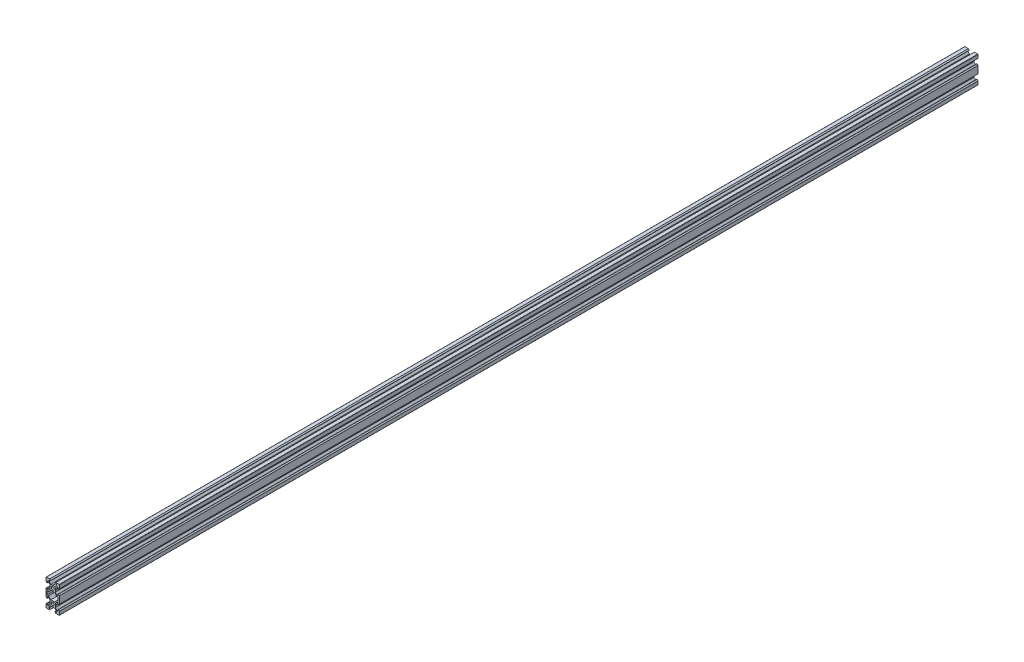
SolidWorks part; units mm, degrees
material "6061-T6 (SS)"
ref_plane "Front Plane" through (0, 0, 0) normal (0, 0, 1) x (1, 0, 0)
ref_plane "Top Plane" through (0, 0, 0) normal (0, 1, 0) x (1, 0, 0)
ref_plane "Right Plane" through (0, 0, 0) normal (1, 0, 0) x (0, 0, -1)
sketch "Sketch1" plane through (0, 0, 0) normal (0, 0, 1) x (1, 0, 0)
  line L0 (0, 0) -> (10, 0) construction
  line L1 (9.5, -20) -> (-9.5, -20)
  line L2 (10, -19.5) -> (10, 19.5)
  line L3 (9.5, 20) -> (-9.5, 20)
  line L4 (-10, -19.5) -> (-10, 19.5)
  line L5 (10, -20) -> (-10, 20) construction
  line L6 (10, 20) -> (-10, -20) construction
  circle A0 centre (0, 10) radius 2.1
  circle A1 centre (0, -10) radius 2.1
  arc A2 (-9.5, -20) -> (-10, -19.5) centre (-9.5, -19.5) cw
  arc A3 (9.5, -20) -> (10, -19.5) centre (9.5, -19.5) ccw
  arc A4 (10, 19.5) -> (9.5, 20) centre (9.5, 19.5) ccw
  arc A5 (-9.5, 20) -> (-10, 19.5) centre (-9.5, 19.5) ccw
  point P0 (0, 0)
  line B0 (0, 10) -> (0, 20) construction
  line B1 (0, 13.69) -> (-0.21, 13.9)
  line B2 (-0.21, 13.9) -> (-2.8393, 13.9)
  line B3 (-2.8393, 13.9) -> (-5.5, 16.5607)
  line B4 (-5.5, 16.5607) -> (-5.5, 18.2)
  line B5 (-5.5, 18.2) -> (-3.125, 18.2)
  line B6 (-3.125, 18.2) -> (-3.125, 18.545)
  line B7 (-3.125, 18.545) -> (-4.58, 20)
  line B8 (-4.58, 20) -> (4.58, 20)
  line B9 (0, 10) -> (-5.9132, 15.9132) construction
  line B10 (3.125, 18.545) -> (4.58, 20)
  line B11 (3.125, 18.2) -> (3.125, 18.545)
  line B12 (5.5, 18.2) -> (3.125, 18.2)
  line B13 (5.5, 16.5607) -> (5.5, 18.2)
  line B14 (2.8393, 13.9) -> (5.5, 16.5607)
  line B15 (0.21, 13.9) -> (2.8393, 13.9)
  line B16 (0, 13.69) -> (0.21, 13.9)
  line B17 (0, 10) -> (-10, 10) construction
  line B18 (-3.69, 10) -> (-3.9, 9.79)
  line B19 (-3.9, 9.79) -> (-3.9, 7.1607)
  line B20 (-3.9, 7.1607) -> (-6.5607, 4.5)
  line B21 (-6.5607, 4.5) -> (-8.2, 4.5)
  line B22 (-8.2, 4.5) -> (-8.2, 6.875)
  line B23 (-8.2, 6.875) -> (-8.545, 6.875)
  line B24 (-8.545, 6.875) -> (-10, 5.42)
  line B25 (-10, 5.42) -> (-10, 14.58)
  line B26 (0, 10) -> (-5.9132, 4.0868) construction
  line B27 (-8.545, 13.125) -> (-10, 14.58)
  line B28 (-8.2, 13.125) -> (-8.545, 13.125)
  line B29 (-8.2, 15.5) -> (-8.2, 13.125)
  line B30 (-6.5607, 15.5) -> (-8.2, 15.5)
  line B31 (-3.9, 12.8393) -> (-6.5607, 15.5)
  line B32 (-3.9, 10.21) -> (-3.9, 12.8393)
  line B33 (-3.69, 10) -> (-3.9, 10.21)
  line B34 (0, -10) -> (-10, -10) construction
  line B35 (-3.69, -10) -> (-3.9, -10.21)
  line B36 (-3.9, -10.21) -> (-3.9, -12.8393)
  line B37 (-3.9, -12.8393) -> (-6.5607, -15.5)
  line B38 (-6.5607, -15.5) -> (-8.2, -15.5)
  line B39 (-8.2, -15.5) -> (-8.2, -13.125)
  line B40 (-8.2, -13.125) -> (-8.545, -13.125)
  line B41 (-8.545, -13.125) -> (-10, -14.58)
  line B42 (-10, -14.58) -> (-10, -5.42)
  line B43 (0, -10) -> (-5.9132, -15.9132) construction
  line B44 (-8.545, -6.875) -> (-10, -5.42)
  line B45 (-8.2, -6.875) -> (-8.545, -6.875)
  line B46 (-8.2, -4.5) -> (-8.2, -6.875)
  line B47 (-6.5607, -4.5) -> (-8.2, -4.5)
  line B48 (-3.9, -7.1607) -> (-6.5607, -4.5)
  line B49 (-3.9, -9.79) -> (-3.9, -7.1607)
  line B50 (-3.69, -10) -> (-3.9, -9.79)
  line B51 (0, -10) -> (0, -20) construction
  line B52 (0, -13.69) -> (0.21, -13.9)
  line B53 (0.21, -13.9) -> (2.8393, -13.9)
  line B54 (2.8393, -13.9) -> (5.5, -16.5607)
  line B55 (5.5, -16.5607) -> (5.5, -18.2)
  line B56 (5.5, -18.2) -> (3.125, -18.2)
  line B57 (3.125, -18.2) -> (3.125, -18.545)
  line B58 (3.125, -18.545) -> (4.58, -20)
  line B59 (4.58, -20) -> (-4.58, -20)
  line B60 (0, -10) -> (5.9132, -15.9132) construction
  line B61 (-3.125, -18.545) -> (-4.58, -20)
  line B62 (-3.125, -18.2) -> (-3.125, -18.545)
  line B63 (-5.5, -18.2) -> (-3.125, -18.2)
  line B64 (-5.5, -16.5607) -> (-5.5, -18.2)
  line B65 (-2.8393, -13.9) -> (-5.5, -16.5607)
  line B66 (-0.21, -13.9) -> (-2.8393, -13.9)
  line B67 (0, -13.69) -> (-0.21, -13.9)
  line B68 (0, -10) -> (10, -10) construction
  line B69 (3.69, -10) -> (3.9, -9.79)
  line B70 (3.9, -9.79) -> (3.9, -7.1607)
  line B71 (3.9, -7.1607) -> (6.5607, -4.5)
  line B72 (6.5607, -4.5) -> (8.2, -4.5)
  line B73 (8.2, -4.5) -> (8.2, -6.875)
  line B74 (8.2, -6.875) -> (8.545, -6.875)
  line B75 (8.545, -6.875) -> (10, -5.42)
  line B76 (10, -5.42) -> (10, -14.58)
  line B77 (0, -10) -> (5.9132, -4.0868) construction
  line B78 (8.545, -13.125) -> (10, -14.58)
  line B79 (8.2, -13.125) -> (8.545, -13.125)
  line B80 (8.2, -15.5) -> (8.2, -13.125)
  line B81 (6.5607, -15.5) -> (8.2, -15.5)
  line B82 (3.9, -12.8393) -> (6.5607, -15.5)
  line B83 (3.9, -10.21) -> (3.9, -12.8393)
  line B84 (3.69, -10) -> (3.9, -10.21)
  line B85 (0, 10) -> (10, 10) construction
  line B86 (3.69, 10) -> (3.9, 10.21)
  line B87 (3.9, 10.21) -> (3.9, 12.8393)
  line B88 (3.9, 12.8393) -> (6.5607, 15.5)
  line B89 (6.5607, 15.5) -> (8.2, 15.5)
  line B90 (8.2, 15.5) -> (8.2, 13.125)
  line B91 (8.2, 13.125) -> (8.545, 13.125)
  line B92 (8.545, 13.125) -> (10, 14.58)
  line B93 (10, 14.58) -> (10, 5.42)
  line B94 (0, 10) -> (5.9132, 15.9132) construction
  line B95 (8.545, 6.875) -> (10, 5.42)
  line B96 (8.2, 6.875) -> (8.545, 6.875)
  line B97 (8.2, 4.5) -> (8.2, 6.875)
  line B98 (6.5607, 4.5) -> (8.2, 4.5)
  line B99 (3.9, 7.1607) -> (6.5607, 4.5)
  line B100 (3.9, 9.79) -> (3.9, 7.1607)
  line B101 (3.69, 10) -> (3.9, 9.79)
  line B102 (-8.2, -2.7) -> (-8.2, 2.7)
  line B103 (-8.2, 2.7) -> (-6.2393, 2.7)
  line B104 (-6.2393, 2.7) -> (-2.8393, 6.1)
  line B105 (-2.8393, 6.1) -> (2.8393, 6.1)
  line B106 (0, 6.1) -> (0, 0) construction
  line B107 (0, 0) -> (-8.2, 0) construction
  line B108 (6.2393, 2.7) -> (2.8393, 6.1)
  line B109 (8.2, 2.7) -> (6.2393, 2.7)
  line B110 (8.2, -2.7) -> (8.2, 2.7)
  line B111 (8.2, -2.7) -> (6.2393, -2.7)
  line B112 (6.2393, -2.7) -> (2.8393, -6.1)
  line B113 (-2.8393, -6.1) -> (2.8393, -6.1)
  line B114 (-6.2393, -2.7) -> (-2.8393, -6.1)
  line B115 (-8.2, -2.7) -> (-6.2393, -2.7)
  line B116 (0, 6.1) -> (0, 10) construction
  line B117 (0, 10) -> (-5.0927, 4.9073) construction
  dimension "D4" = 4.2
  dimension "D5" = 0.5
  dimension "D1" = 20
  dimension "D2" = 40
  dimension "D3" = 20
sketch_block_instance "V Slot 1-4"
sketch_block "V Slot 1" parameters "D1"=10, "D2"=11, "D3"=4.3, "D4"=1.8, "D5"=0.21, "D6"=45, "D7"=9.16, "D8"=1.5, "D9"=6.25
sketch_block_instance "V Slot 1-5"
sketch_block_instance "V Slot 1-6"
sketch_block_instance "V Slot 1-7"
sketch_block_instance "V Slot 1-8"
sketch_block_instance "V Slot 1-9"
sketch_block_instance "Center Cutout 1-1"
sketch_block "Center Cutout 1" parameters "D1"=5.4, "D2"=12.2, "D3"=8.2, "D4"=45, "D5"=10, "D6"=1.5
extrude "Boss-Extrude1" add sketch "Sketch1" along normal blind 1371.6 contours B101 B86 B87 B88 B89 B90 B91 B92 L2 A4 L3 B10 B11 B12 B13 B14 B15 B16 B1 B2 B3 B4 B5 B6 B7 A5 L4 B27 B28 B29 B30 B31 B32 B33 B18 B19 B20 B21 B22 B23 B24 B44 B45 B46 B47 B48 B49 B50 B35
